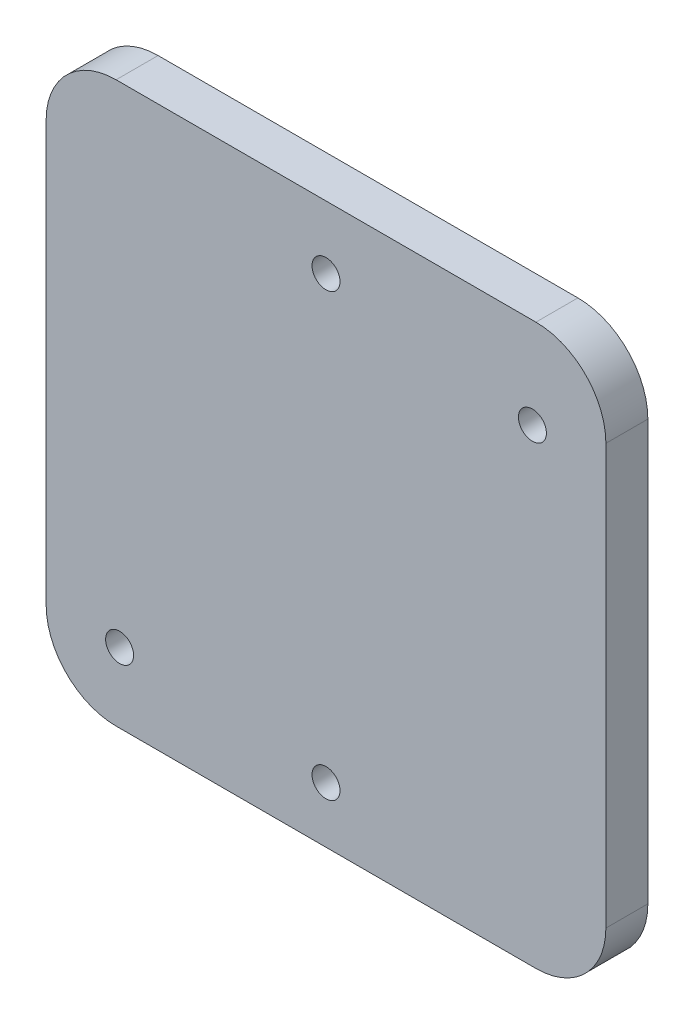
SolidWorks part; units mm, degrees
ref_plane "Front Plane" through (0, 0, 0) normal (0, 0, 1) x (1, 0, 0)
ref_plane "Top Plane" through (0, 0, 0) normal (0, 1, 0) x (1, 0, 0)
ref_plane "Right Plane" through (0, 0, 0) normal (1, 0, 0) x (0, 0, -1)
sketch "Sketch1" plane through (0, 0, 0) normal (0, 0, 1) x (1, 0, 0)
  line L1 (-30, 40) -> (30, 40)
  line L2 (-40, 30) -> (-40, -30)
  line L3 (-30, -40) -> (30, -40)
  line L4 (40, 30) -> (40, -30)
  line L5 (-40, 40) -> (40, -40) construction
  line L6 (-40, -40) -> (40, 40) construction
  arc A0 (-30, 40) -> (-40, 30) centre (-30, 30) ccw
  arc A1 (30, 40) -> (40, 30) centre (30, 30) cw
  arc A2 (30, -40) -> (40, -30) centre (30, -30) ccw
  arc A3 (-30, -40) -> (-40, -30) centre (-30, -30) cw
  point P0 (0, 0)
  dimension "D3" = 10
  dimension "D4" = 10
  dimension "D1" = 80
  dimension "D2" = 80
extrude "Body" add sketch "Sketch1" along normal blind 6
sketch "Sketch3" plane through (0, 0, 6) normal (0, 0, 1) x (1, 0, 0)
  line L0 (0, -32) -> (0, 0) construction
  line L4 (0, 0) -> (0, 31) construction
  line L5 (29.5, 27) -> (0, 27) construction
  line L7 (-29.5, -30) -> (0, -30) construction
  circle A0 centre (0, 31) radius 2
  circle A1 centre (29.5, 27) radius 2
  circle A2 centre (0, -32) radius 2
  circle A3 centre (-29.5, -30) radius 2
  dimension "D2" = 4
  dimension "D5" = 4
  dimension "D1" = 31
  dimension "D3" = 32
  dimension "D4" = 29.5
  dimension "D6" = 27
  dimension "D7" = 29.5
  dimension "D8" = 30
extrude "Mounting holes" cut sketch "Sketch3" against normal through all
